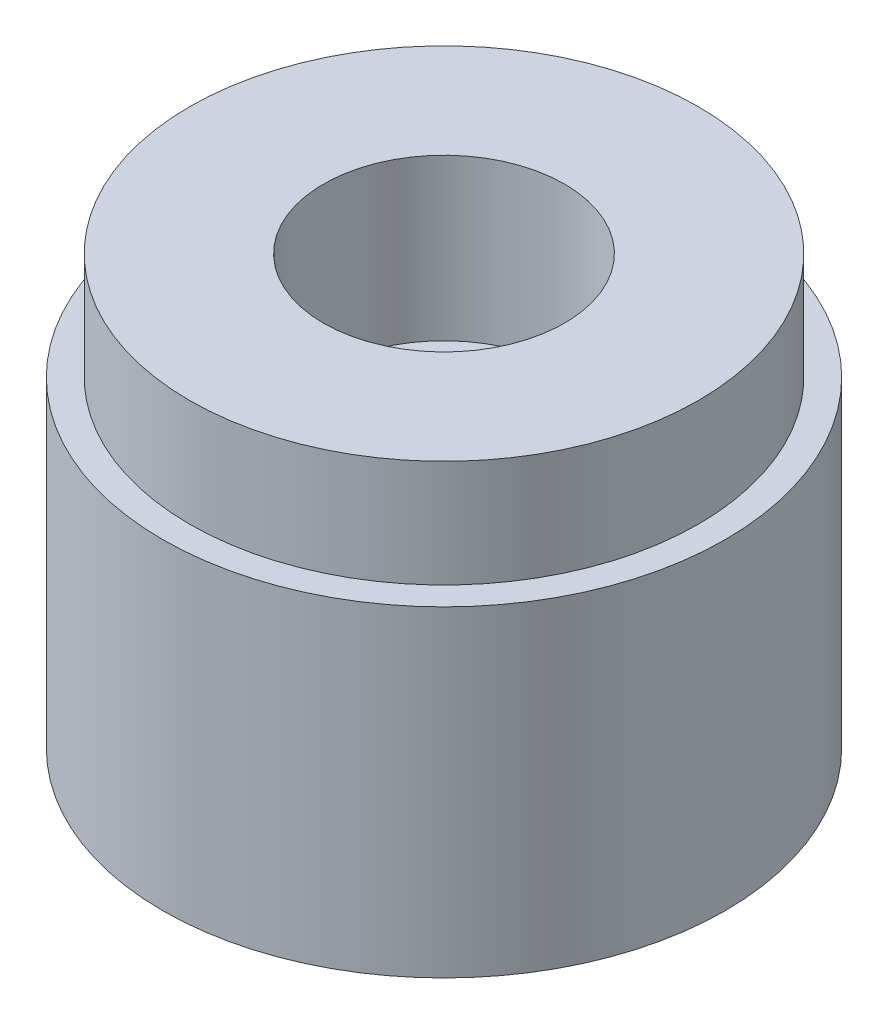
SolidWorks part; units mm, degrees
ref_plane "Plan de face" through (0, 0, 0) normal (0, 0, 1) x (1, 0, 0)
ref_plane "Plan de dessus" through (0, 0, 0) normal (0, 1, 0) x (1, 0, 0)
ref_plane "Plan de droite" through (0, 0, 0) normal (1, 0, 0) x (0, 0, -1)
sketch "Esquisse1" plane through (0, 0, 0) normal (0, 0, 1) x (1, 0, 0)
  line L0 (1.35, 0) -> (1.35, 8)
  line L1 (1.35, 8) -> (4.75, 8)
  line L2 (4.75, 8) -> (4.75, 6)
  line L3 (4.75, 6) -> (5.25, 6)
  line L4 (5.25, 6) -> (5.25, 0)
  line L5 (5.25, 0) -> (1.35, 0)
  line L6 (0, 0) -> (0, 11.4453) construction
  line L7 (1.35, 0) -> (0, 0) construction
  dimension "D1" = 2.7
  dimension "D2" = 9.5
  dimension "D3" = 10.5
  dimension "D4" = 2
  dimension "D5" = 6
revolve "Révolution1" add sketch "Esquisse1" angle 360 about L6
sketch "Esquisse2" plane through (0, 8, 0) normal (0, 1, 0) x (1, 0, 0)
  circle A0 centre (0, 0) radius 2.25
  dimension "D1" = 4.5
extrude "Enlèv. mat.-Extru.1" cut sketch "Esquisse2" against normal blind 3
